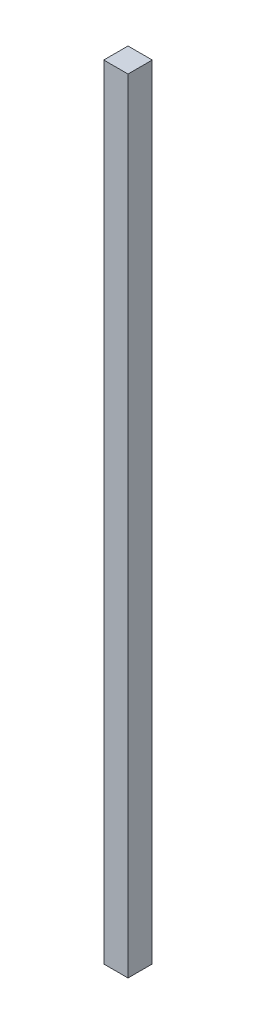
SolidWorks part; units mm, degrees
material "Oak"
ref_plane "Front Plane" through (0, 0, 0) normal (0, 0, 1) x (1, 0, 0)
ref_plane "Top Plane" through (0, 0, 0) normal (0, 1, 0) x (1, 0, 0)
ref_plane "Right Plane" through (0, 0, 0) normal (1, 0, 0) x (0, 0, -1)
sketch "Sketch1" plane through (0, 0, 0) normal (0, 0, 1) x (1, 0, 0)
  line L1 (-1129.03, -36451.54) -> (1129.03, -36451.54)
  line L2 (-1129.03, -36451.54) -> (-1129.03, 36451.54)
  line L3 (-1129.03, 36451.54) -> (1129.03, 36451.54)
  line L4 (1129.03, -36451.54) -> (1129.03, 36451.54)
  line L5 (-1129.03, -36451.54) -> (1129.03, 36451.54) construction
  line L6 (-1129.03, 36451.54) -> (1129.03, -36451.54) construction
  point P0 (0, 0)
  dimension "D1" = 72903.08
  dimension "D2" = 2258.06
extrude "Boss-Extrude1" add sketch "Sketch1" along normal blind 2258.06
scale "Scale1" scale about centroid uniform scaling yes scale factor 0.03937
